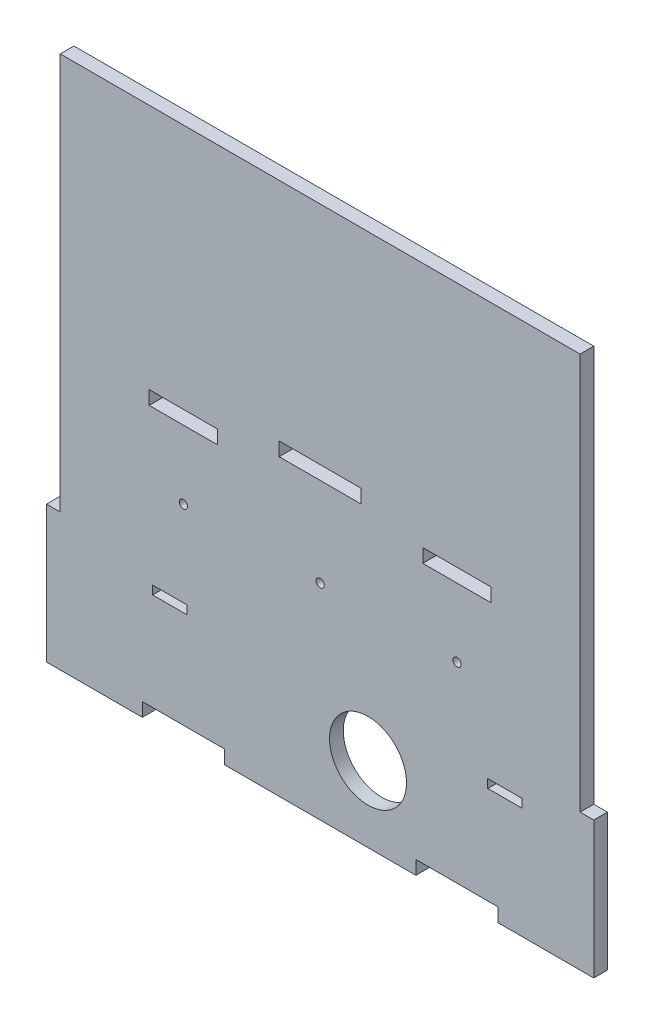
SolidWorks part; units mm, degrees
ref_plane "Front Plane" through (0, 0, 0) normal (0, 0, 1) x (1, 0, 0)
ref_plane "Top Plane" through (0, 0, 0) normal (0, 1, 0) x (1, 0, 0)
ref_plane "Right Plane" through (0, 0, 0) normal (1, 0, 0) x (0, 0, -1)
sketch "Sketch1" plane through (0, 0, 0) normal (0, 0, 1) x (1, 0, 0)
  line L0 (68.58, 44.45) -> (68.58, 50.8)
  line L1 (-96.52, 0) -> (96.52, 0)
  line L2 (-96.52, 0) -> (-96.52, 198.12)
  line L3 (-96.52, 198.12) -> (96.52, 198.12)
  line L4 (96.52, 0) -> (96.52, 198.12)
  line L5 (-101.6, 203.2) -> (-59.69, 203.2) construction
  line L6 (96.52, 5.08) -> (66.04, 5.08) construction
  line L7 (-66.04, 0) -> (-35.56, 0)
  line L8 (-66.04, 0) -> (-66.04, 5.08)
  line L9 (-66.04, 5.08) -> (-35.56, 5.08)
  line L10 (-35.56, 0) -> (-35.56, 5.08)
  line L11 (-66.04, 5.08) -> (-96.52, 5.08)
  line L12 (35.56, 0) -> (66.04, 0)
  line L13 (35.56, 0) -> (35.56, 5.08)
  line L14 (35.56, 5.08) -> (66.04, 5.08)
  line L15 (66.04, 0) -> (66.04, 5.08)
  line L16 (66.04, 5.08) -> (96.52, 5.08)
  line L17 (-96.52, 50.8) -> (96.52, 50.8)
  line L18 (-55.88, 44.45) -> (-55.88, 50.8)
  line L19 (-62.23, 44.45) -> (-49.53, 44.45)
  line L20 (-62.23, 44.45) -> (-62.23, 41.275)
  line L21 (-62.23, 41.275) -> (-49.53, 41.275)
  line L22 (-49.53, 44.45) -> (-49.53, 41.275)
  line L23 (62.23, 44.45) -> (74.93, 44.45)
  line L24 (62.23, 44.45) -> (62.23, 41.275)
  line L25 (62.23, 41.275) -> (74.93, 41.275)
  line L26 (74.93, 44.45) -> (74.93, 41.275)
  line L27 (17.78, 50.8) -> (17.78, 27.94)
  line L28 (96.52, 50.8) -> (96.52, 0) construction
  line L29 (-50.8, 76.2) -> (0, 76.2)
  line L30 (0, 76.2) -> (50.8, 76.2)
  line L31 (0, 76.2) -> (0, 50.8)
  line L32 (-38.1, 101.6) -> (38.1, 101.6)
  line L33 (-63.5, 101.6) -> (-38.1, 101.6)
  line L34 (-63.5, 101.6) -> (-63.5, 106.68)
  line L35 (-63.5, 106.68) -> (-38.1, 106.68)
  line L36 (-38.1, 101.6) -> (-38.1, 106.68)
  line L37 (38.1, 101.6) -> (63.5, 101.6)
  line L38 (38.1, 101.6) -> (38.1, 106.68)
  line L39 (38.1, 106.68) -> (63.5, 106.68)
  line L40 (63.5, 101.6) -> (63.5, 106.68)
  line L41 (0, 101.6) -> (0, 76.2)
  circle A0 centre (17.78, 27.94) radius 14.2875
  circle A1 centre (-50.8, 76.2) radius 1.524
  circle A2 centre (0, 76.2) radius 1.524
  circle A3 centre (50.8, 76.2) radius 1.524
  point P44 (68.58, 44.45)
  dimension "D4" = 28.575
  dimension "D13" = 3.048
  dimension "D1" = 5.08
  dimension "D2" = 30.48
  dimension "D3" = 30.48
  dimension "D5" = 12.7
  dimension "D6" = 12.7
  dimension "D7" = 3.175
  dimension "D8" = 22.86
  dimension "D9" = 6.35
  dimension "D10" = 27.94
  dimension "D11" = 40.64
  dimension "D12" = 78.74
  dimension "D14" = 50.8
  dimension "D15" = 25.4
  dimension "D16" = 5.08
  dimension "D17" = 25.4
  dimension "D18" = 76.2
  dimension "D19" = 25.4
extrude "Boss-Extrude1" add sketch "Sketch1" along normal blind 5.08
sketch "Sketch2" plane through (0, 0, 5.08) normal (0, 0, 1) x (1, 0, 0)
  line L1 (101.6, 50.8) -> (96.52, 50.8)
  line L2 (101.6, 50.8) -> (101.6, 0)
  line L3 (101.6, 0) -> (96.52, 0)
  line L4 (96.52, 50.8) -> (96.52, 0)
  line L5 (-101.6, 50.8) -> (-96.52, 50.8)
  line L6 (-101.6, 50.8) -> (-101.6, 0)
  line L7 (-101.6, 0) -> (-96.52, 0)
  line L8 (-96.52, 50.8) -> (-96.52, 0)
extrude "Boss-Extrude2" add sketch "Sketch2" against normal blind 5.08 contours L6 L5 L8 L7 | L2 L1 L4 L3
sketch "Sketch3" plane through (0, 0, 5.08) normal (0, 0, 1) x (1, 0, 0)
  line L0 (15.24, 111.76) -> (50.8, 111.76)
  line L1 (-15.24, 114.3) -> (15.24, 114.3)
  line L2 (-15.24, 114.3) -> (-15.24, 109.22)
  line L3 (-15.24, 109.22) -> (15.24, 109.22)
  line L4 (15.24, 114.3) -> (15.24, 109.22)
  line L5 (50.8, 111.76) -> (50.8, 106.68)
  line L6 (38.1, 106.68) -> (63.5, 106.68) construction
  line L7 (-15.24, 111.76) -> (-50.8, 111.76)
  line L8 (-50.8, 111.76) -> (-50.8, 106.68)
  line L9 (-63.5, 106.68) -> (-38.1, 106.68) construction
  dimension "D1" = 5.08
  dimension "D2" = 30.48
  dimension "D3" = 5.08
extrude "Cut-Extrude1" cut sketch "Sketch3" against normal blind 5.08 contours L4 L1 L2 L3
